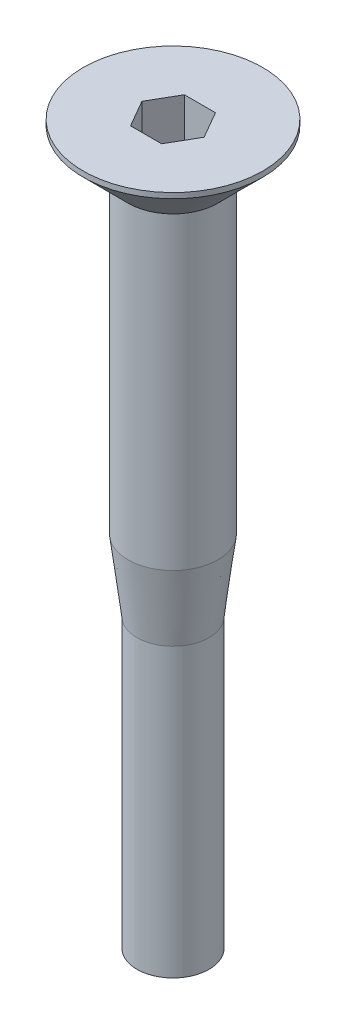
SolidWorks part; units mm, degrees
ref_plane "Vorne" through (0, 0, 0) normal (0, 0, 1) x (1, 0, 0)
ref_plane "Oben" through (0, 0, 0) normal (0, 1, 0) x (1, 0, 0)
ref_plane "Rechts" through (0, 0, 0) normal (1, 0, 0) x (0, 0, -1)
sketch "Skizze1" plane through (0, 0, 0) normal (0, 0, 1) x (1, 0, 0)
  line L0 (0, 0) -> (5, 0)
  line L1 (5, 0) -> (5, -0.3)
  line L2 (5, -0.3) -> (2.5, -2.8)
  line L3 (2.5, -2.8) -> (2.5, -20)
  line L4 (2.5, -20) -> (2.0095, -24)
  line L5 (2.0095, -24) -> (2.0095, -40)
  line L6 (2.0095, -40) -> (0, -40)
  line L7 (0, -40) -> (0, 0)
  line L8 (0, 0) -> (0, -40) construction
  dimension "DK" = 4.019
  dimension "D2" = 45
  dimension "DG" = 5
  dimension "DA" = 10
  dimension "K" = 2.8
  dimension "LS" = 20
  dimension "LG" = 24
  dimension "L" = 40
revolve "Basis-Rotation" add sketch "Skizze1" angle 360 about L8
sketch "Skizze2" plane through (0, 0, 0) normal (0, 1, 0) x (-1, 0, 0)
  line L0 (1.7321, 0) -> (-1.7321, 0) construction
  line L1 (0, 1.5) -> (0, -1.5) construction
  line L2 (0.866, -1.5) -> (-0.866, -1.5)
  line L3 (-0.866, -1.5) -> (-1.7321, 0)
  line L4 (0.866, -1.5) -> (1.7321, 0)
  line L5 (0.866, 1.5) -> (1.7321, 0)
  line L6 (-0.866, 1.5) -> (-1.7321, 0)
  line L7 (0.866, 1.5) -> (-0.866, 1.5)
  dimension "D2" = 120
extrude "Schnitt-Linear austragen1" cut sketch "Skizze2" against normal blind 5.3
